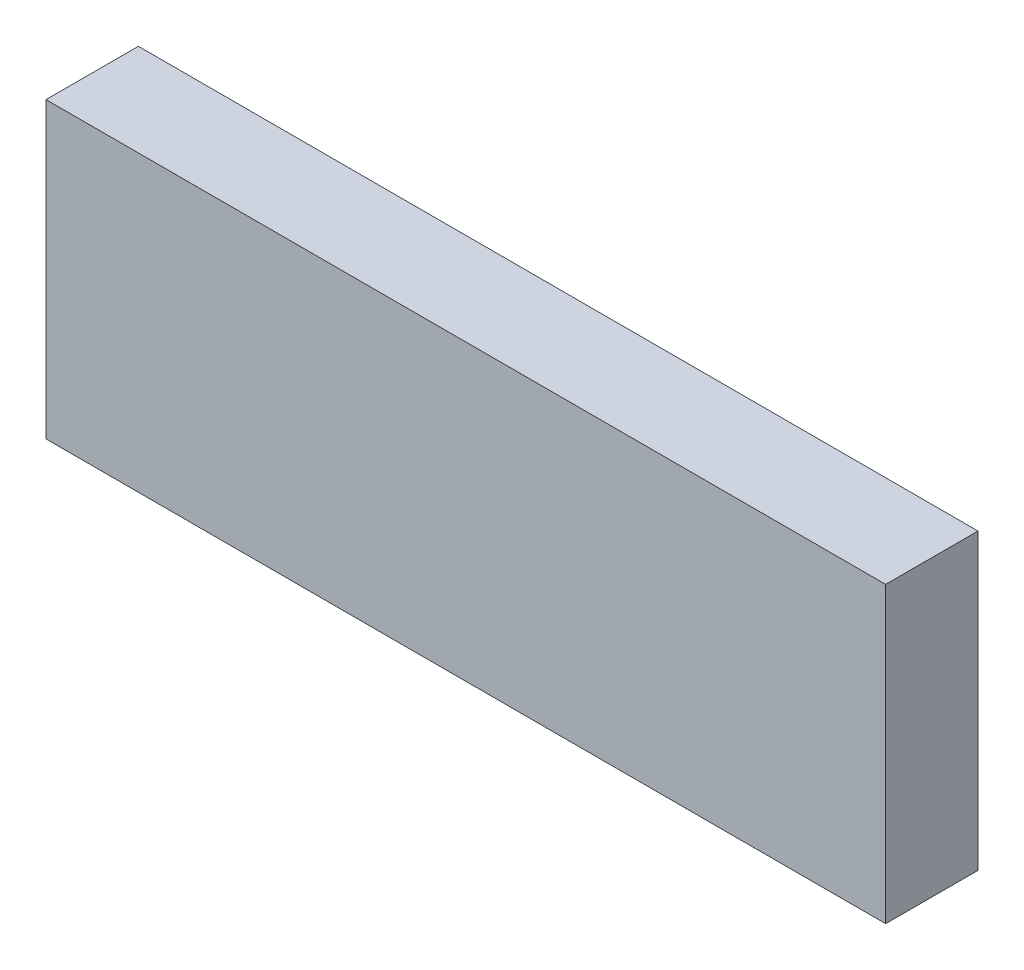
SolidWorks part; units mm, degrees
ref_plane "Front Plane" through (0, 0, 0) normal (0, 0, 1) x (1, 0, 0)
ref_plane "Top Plane" through (0, 0, 0) normal (0, 1, 0) x (1, 0, 0)
ref_plane "Right Plane" through (0, 0, 0) normal (1, 0, 0) x (0, 0, -1)
sketch "Sketch1" plane through (0, 0, 0) normal (0, 0, 1) x (1, 0, 0)
  line L1 (-100, 35) -> (100, 35)
  line L2 (-100, 35) -> (-100, -35)
  line L3 (-100, -35) -> (100, -35)
  line L4 (100, 35) -> (100, -35)
  line L5 (-100, 35) -> (100, -35) construction
  line L6 (-100, -35) -> (100, 35) construction
  point P0 (0, 0)
  dimension "D1" = 70
  dimension "D2" = 200
extrude "Boss-Extrude1" add sketch "Sketch1" along normal blind 22
